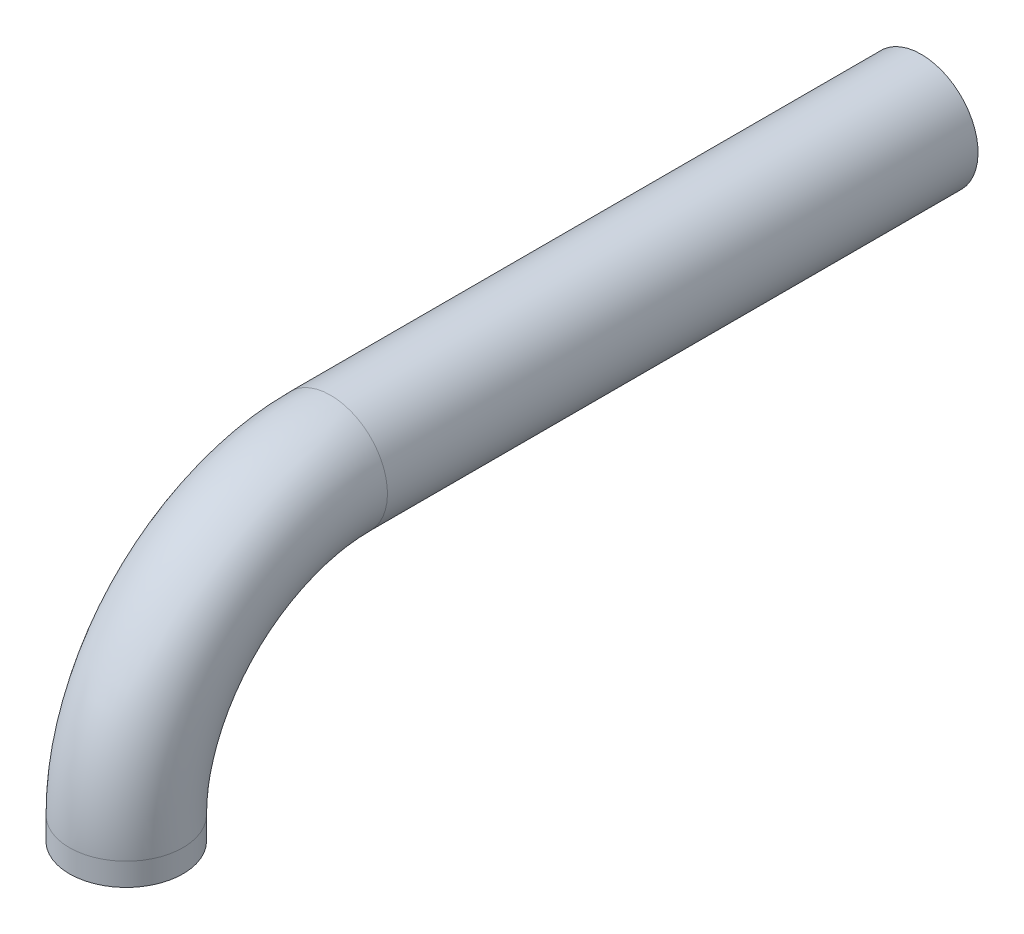
SolidWorks part; units mm, degrees
ref_plane "Front" through (0, 0, 0) normal (0, 0, 1) x (1, 0, 0)
ref_plane "Top" through (0, 0, 0) normal (0, 1, 0) x (1, 0, 0)
ref_plane "Right" through (0, 0, 0) normal (1, 0, 0) x (0, 0, -1)
sketch "Skizze1" plane through (0, 0, 0) normal (1, 0, 0) x (0, 0, -1)
  line L0 (0, 0) -> (0, 0.5)
  line L1 (4.5, 5) -> (17.5, 5)
  arc A0 (0, 0.5) -> (4.5, 5) centre (4.5, 0.5) cw
  point P6 (0, 5)
  dimension "D3" = 4.5
  dimension "D1" = 5
  dimension "D2" = 17.5
sketch "Skizze2" plane through (0, 0, 0) normal (0, 1, 0) x (1, 0, 0)
  circle A0 centre (0, 0) radius 1
  circle A1 centre (0, 0) radius 1.25
  dimension "D1" = 2.5
  dimension "D2" = 2
sweep "Austragung1" add profiles "Skizze2" path "Skizze1"
